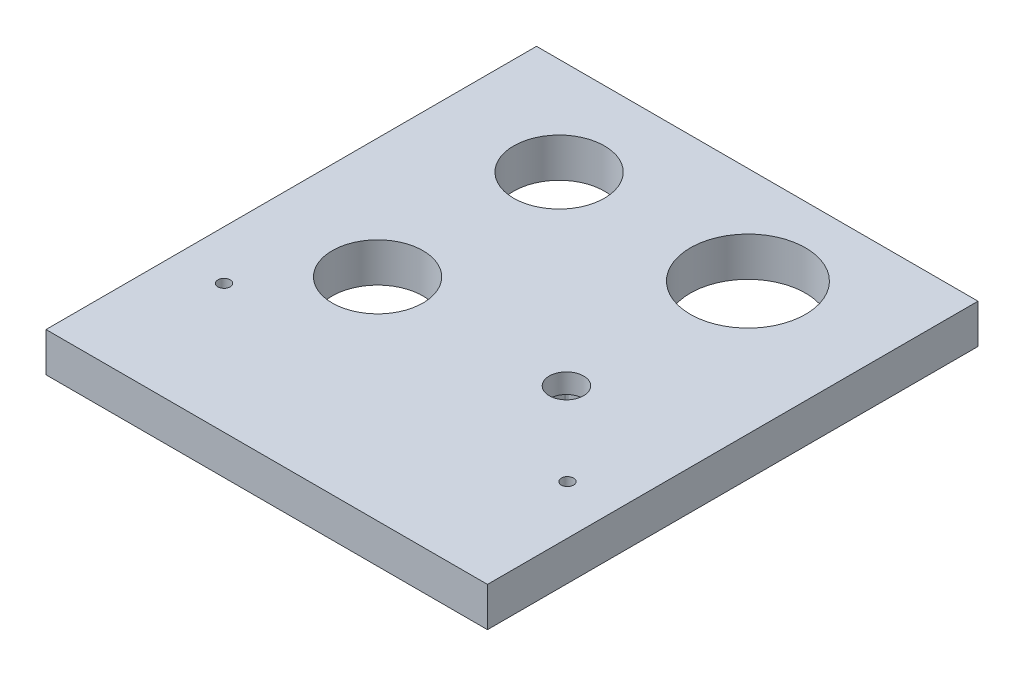
SolidWorks part; units mm, degrees
material "1060-H18"
ref_plane "Спереди" through (0, 0, 0) normal (0, 0, 1) x (1, 0, 0)
ref_plane "Сверху" through (0, 0, 0) normal (0, 1, 0) x (1, 0, 0)
ref_plane "Справа" through (0, 0, 0) normal (1, 0, 0) x (0, 0, -1)
sketch "Эскиз1" plane through (0, 0, 0) normal (0, 1, 0) x (1, 0, 0)
  line L1 (45, 50) -> (-45, 50)
  line L2 (45, 50) -> (45, -50)
  line L3 (45, -50) -> (-45, -50)
  line L4 (-45, 50) -> (-45, -50)
  line L5 (45, 50) -> (-45, -50) construction
  line L6 (45, -50) -> (-45, 50) construction
  point P0 (0, 0)
  dimension "D1" = 100
  dimension "D2" = 90
extrude "Бобышка-Вытянуть1" add sketch "Эскиз1" along normal blind 8
hole_wizard "Отверстие обработанное метчиком M20x1,51" positions "Эскиз2" profile "Эскиз3" tap size "M20x1,5" standard "GOST" end condition through all
sketch "Эскиз2" plane through (0, 8, 0) normal (0, 1, 0) x (1, 0, 0)
  line L0 (-20.5, -6.9) -> (18, -6.9) construction
  line L1 (18, -6.9) -> (18, 30.1) construction
  line L2 (18, 30.1) -> (-20.5, 30.1) construction
  line L3 (-20.5, 30.1) -> (-20.5, -6.9) construction
  line L5 (45, 50) -> (-45, 50) construction
  line L6 (45, -50) -> (45, 50) construction
  point P28 (18, 30.1)
  point P34 (-20.5, -6.9)
  point P38 (-20.5, 30.1)
  dimension "D1" = 37
  dimension "D2" = 38.5
  dimension "D3" = 19.9
  dimension "D4" = 27
sketch "Эскиз3" plane through (-20.5, 8, -30.1) normal (1, 0, 0) x (0, 0, 1)
  line L0 (0, 0) -> (0, 8)
  line L1 (0, 8) -> (9.25, 8)
  line L2 (9.25, 8) -> (9.25, 0)
  line L5 (9.25, 0) -> (0, 0)
  line L11 (0, -6.35) -> (0, 107.95) construction
  dimension "Диаметр проходного сверла" = 18.5
  dimension "Глубина проходного сверла" = 8
cosmetic thread "Отверстие резьбы11" parameters "D2"=20
cosmetic thread "Отверстие резьбы12" parameters "D2"=20
hole_wizard "Отверстие обработанное метчиком M25x1,51" positions "Эскиз4" profile "Эскиз5" tap size "M25x1,5" standard "GOST" end condition through all
sketch "Эскиз4" plane through (0, 8, 0) normal (0, 1, 0) x (1, 0, 0)
  point P16 (18, 30.1)
sketch "Эскиз5" plane through (18, 8, -30.1) normal (1, 0, 0) x (0, 0, 1)
  line L0 (0, 0) -> (0, 8)
  line L1 (0, 8) -> (11.75, 8)
  line L2 (11.75, 8) -> (11.75, 0)
  line L5 (11.75, 0) -> (0, 0)
  line L11 (0, -6.35) -> (0, 107.95) construction
  dimension "Диаметр проходного сверла" = 23.5
  dimension "Глубина проходного сверла" = 8
cosmetic thread "Отверстие резьбы14" parameters "D2"=25
sketch "Эскиз6" plane through (0, 0, 0) normal (0, -1, 0) x (1, 0, 0)
  line L5 (22, 10.9) -> (14, 10.9)
  line L6 (22, 10.9) -> (22, 2.9)
  line L7 (22, 2.9) -> (14, 2.9)
  line L8 (14, 10.9) -> (14, 2.9)
  line L9 (22, 10.9) -> (14, 2.9) construction
  line L10 (22, 2.9) -> (14, 10.9) construction
  line L12 (18, 6.9) -> (18, -30.1) construction
  line L13 (18, 6.9) -> (-20.5, 6.9) construction
  point P0 (18, 6.9)
  dimension "D1" = 8
extrude "Вырез-Вытянуть1" cut sketch "Эскиз6" against normal offset from surface (4 mm away) 4 up to face at (18, 8, -18.35)
fillet "Скругление1" radius 0.3 4 edges at (14, 2, 10.9) (14, 2, 2.9) (22, 2, 2.9) (22, 2, 10.9)
sketch "Эскиз7" plane through (0, 4, 0) normal (0, -1, 0) x (1, 0, 0)
  line L0 (18, 6.9) -> (22, 6.9) construction
  line L1 (22, 3.2) -> (22, 10.6) construction
  line L3 (14.3, 10.9) -> (21.7, 10.9) construction
  line L4 (18, 10.9) -> (18, 6.9) construction
  circle A0 centre (18, 6.9) radius 3.5
  dimension "D1" = 7
extrude "Вырез-Вытянуть2" cut sketch "Эскиз7" against normal blind 9
hole_wizard "Отверстие обработанное метчиком M31" positions "Эскиз8" profile "Эскиз9" tap size "M3" standard "GOST"
sketch "Эскиз8" plane through (0, 8, 0) normal (0, 1, 0) x (1, 0, 0)
  line L1 (35, -23.7) -> (-35, -23.7) construction
  line L3 (-45, -50) -> (45, -50) construction
  line L4 (0, -23.7) -> (0, -50) construction
  point P4 (35, -23.7)
  point P6 (-35, -23.7)
  dimension "D1" = 26.3
  dimension "D2" = 70
sketch "Эскиз9" plane through (35, 8, 23.7) normal (1, 0, 0) x (0, 0, 1)
  line L0 (0, 0) -> (0, 9.2511)
  line L1 (0, 9.2511) -> (1.25, 8.5)
  line L2 (1.25, 8.5) -> (1.25, 0)
  line L5 (1.25, 0) -> (0, 0)
  line L10 (0, 9.2511) -> (-1.25, 8.5) construction
  line L11 (0, -6.35) -> (0, 107.95) construction
  dimension "Диаметр сверла" = 2.5
  dimension "Глубина сверла" = 8.5
  dimension "Угол заточки сверла" = 118
cosmetic thread "Отверстие резьбы9" parameters "D1"=6, "D2"=3
cosmetic thread "Отверстие резьбы10" parameters "D1"=6, "D2"=3
